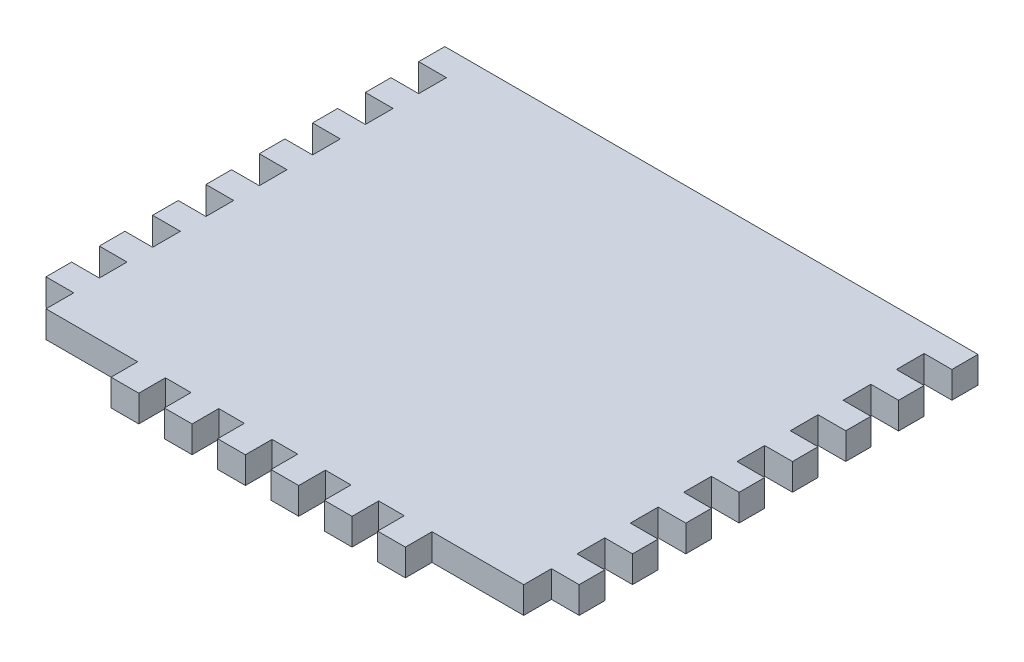
SolidWorks part; units mm, degrees
ref_plane "Front Plane" through (0, 0, 0) normal (0, 0, 1) x (1, 0, 0)
ref_plane "Top Plane" through (0, 0, 0) normal (0, 1, 0) x (1, 0, 0)
ref_plane "Right Plane" through (0, 0, 0) normal (1, 0, 0) x (0, 0, -1)
sketch "Sketch1" plane through (0, 0, 0) normal (0, 1, 0) x (1, 0, 0)
  line L1 (-63.5, -53.975) -> (63.5, -53.975)
  line L2 (-63.5, -53.975) -> (-63.5, 53.975)
  line L3 (-63.5, 53.975) -> (63.5, 53.975)
  line L4 (63.5, -53.975) -> (63.5, 53.975)
  line L5 (-63.5, -53.975) -> (63.5, 53.975) construction
  line L6 (-63.5, 53.975) -> (63.5, -53.975) construction
  line L11 (-41.275, -53.975) -> (41.275, 53.975) construction
  line L12 (-41.275, 53.975) -> (41.275, -53.975) construction
  point P0 (0, 0)
  point P5 (0, 0)
  dimension "D1" = 127
  dimension "D2" = 107.95
extrude "Boss-Extrude1" add sketch "Sketch1" along normal blind 6.35
sketch "Sketch2" plane through (0, 6.35, 0) normal (0, 1, 0) x (1, 0, 0)
  line L37 (22.352, -47.625) -> (28.448, -47.625)
  line L49 (28.448, -47.625) -> (28.448, -54.229)
  line L69 (0, 0) -> (0, -10.121) construction
  line L74 (-63.5, 53.975) -> (-63.5, -53.975) construction
  line L75 (-56.896, 28.448) -> (-63.5, 28.448)
  line L76 (-56.896, 28.448) -> (-56.896, 35.052)
  line L78 (-63.5, 28.448) -> (-63.5, 35.052)
  line L79 (-56.896, 22.479) -> (-63.5, 22.479)
  line L80 (-56.896, 22.479) -> (-56.896, 15.875)
  line L81 (-56.896, 15.875) -> (-63.5, 15.875)
  line L82 (-63.5, 22.479) -> (-63.5, 15.875)
  line L83 (-56.896, 9.779) -> (-63.5, 9.779)
  line L84 (-56.896, 9.779) -> (-56.896, 3.175)
  line L85 (-56.896, 3.175) -> (-63.5, 3.175)
  line L86 (-63.5, 9.779) -> (-63.5, 3.175)
  line L87 (-56.896, -2.921) -> (-63.5, -2.921)
  line L88 (-56.896, -2.921) -> (-56.896, -9.525)
  line L89 (-56.896, -9.525) -> (-63.5, -9.525)
  line L90 (-63.5, -2.921) -> (-63.5, -9.525)
  line L91 (-56.896, -15.621) -> (-63.5, -15.621)
  line L92 (-56.896, -15.621) -> (-56.896, -22.225)
  line L93 (-56.896, -22.225) -> (-63.5, -22.225)
  line L94 (-63.5, -15.621) -> (-63.5, -22.225)
  line L95 (-56.896, -28.321) -> (-63.5, -28.321)
  line L96 (-56.896, -28.321) -> (-56.896, -34.925)
  line L97 (-56.896, -34.925) -> (-63.5, -34.925)
  line L98 (-63.5, -28.321) -> (-63.5, -34.925)
  line L99 (-56.896, -41.021) -> (-63.5, -41.021)
  line L100 (-56.896, -41.021) -> (-56.896, -47.625)
  line L102 (-63.5, -41.021) -> (-63.5, -47.625)
  line L118 (63.5, -41.021) -> (63.5, -47.625)
  line L120 (56.896, -41.021) -> (56.896, -47.625)
  line L121 (56.896, -41.021) -> (63.5, -41.021)
  line L122 (63.5, -28.321) -> (63.5, -34.925)
  line L123 (56.896, -34.925) -> (63.5, -34.925)
  line L124 (56.896, -28.321) -> (56.896, -34.925)
  line L125 (56.896, -28.321) -> (63.5, -28.321)
  line L126 (63.5, -15.621) -> (63.5, -22.225)
  line L127 (56.896, -22.225) -> (63.5, -22.225)
  line L128 (56.896, -15.621) -> (56.896, -22.225)
  line L129 (56.896, -15.621) -> (63.5, -15.621)
  line L130 (63.5, -2.921) -> (63.5, -9.525)
  line L131 (56.896, -9.525) -> (63.5, -9.525)
  line L132 (56.896, -2.921) -> (56.896, -9.525)
  line L133 (56.896, -2.921) -> (63.5, -2.921)
  line L134 (63.5, 9.779) -> (63.5, 3.175)
  line L135 (56.896, 3.175) -> (63.5, 3.175)
  line L136 (56.896, 9.779) -> (56.896, 3.175)
  line L137 (56.896, 9.779) -> (63.5, 9.779)
  line L138 (63.5, 22.479) -> (63.5, 15.875)
  line L139 (56.896, 15.875) -> (63.5, 15.875)
  line L140 (56.896, 22.479) -> (56.896, 15.875)
  line L141 (56.896, 22.479) -> (63.5, 22.479)
  line L150 (-56.896, -53.721) -> (-63.5, -53.721) [skipped]
  line L151 (-56.896, -53.721) -> (-56.896, -60.325) [skipped]
  line L152 (-56.896, -60.325) -> (-63.5, -60.325) [skipped]
  line L153 (-63.5, -53.721) -> (-63.5, -60.325) [skipped]
  line L154 (-63.5, 35.052) -> (-56.896, 35.052)
  line L155 (63.5, 35.052) -> (56.896, 35.052)
  line L156 (63.5, 28.448) -> (63.5, 35.052)
  line L157 (56.896, 28.448) -> (56.896, 35.052)
  line L158 (56.896, 28.448) -> (63.5, 28.448)
  line L159 (-56.896, -47.625) -> (-35.052, -47.625)
  line L160 (-35.052, -47.625) -> (-35.052, -54.229)
  line L161 (-35.052, -54.229) -> (-28.448, -54.229)
  line L162 (-28.448, -54.229) -> (-28.448, -47.625)
  line L163 (-28.448, -47.625) -> (-22.352, -47.625)
  line L164 (-22.352, -47.625) -> (-22.352, -54.229)
  line L165 (-22.352, -54.229) -> (-15.748, -54.229)
  line L166 (-15.748, -54.229) -> (-15.748, -47.625)
  line L167 (-15.748, -47.625) -> (-9.652, -47.625)
  line L168 (-9.652, -47.625) -> (-9.652, -54.229)
  line L169 (-9.652, -54.229) -> (-3.048, -54.229)
  line L170 (-3.048, -54.229) -> (-3.048, -47.625)
  line L171 (-3.048, -47.625) -> (3.048, -47.625)
  line L172 (3.048, -47.625) -> (3.048, -54.229)
  line L173 (3.048, -54.229) -> (9.652, -54.229)
  line L174 (9.652, -54.229) -> (9.652, -47.625)
  line L175 (9.652, -47.625) -> (15.748, -47.625)
  line L176 (15.748, -47.625) -> (15.748, -54.229)
  line L177 (15.748, -54.229) -> (22.352, -54.229)
  line L178 (22.352, -54.229) -> (22.352, -47.625)
  line L180 (-63.5, -47.625) -> (-63.5, -92.545)
  line L181 (-56.896, -47.625) -> (-63.5, -47.625) [skipped]
  line L182 (-63.5, -92.545) -> (63.5, -92.545)
  line L183 (63.5, -92.545) -> (63.5, -47.625)
  line L184 (28.448, -54.229) -> (35.052, -54.229)
  line L185 (35.052, -54.229) -> (35.052, -47.625)
  line L186 (35.052, -47.625) -> (56.896, -47.625)
  line L187 (63.5, 53.975) -> (-63.5, 53.975) construction
  line L188 (63.5, 47.752) -> (56.896, 47.752)
  line L189 (63.5, 41.148) -> (63.5, 47.752)
  line L190 (56.896, 41.148) -> (56.896, 47.752)
  line L191 (56.896, 41.148) -> (63.5, 41.148)
  line L192 (-56.896, 41.148) -> (-63.5, 41.148)
  line L193 (-56.896, 41.148) -> (-56.896, 47.752)
  line L194 (-63.5, 41.148) -> (-63.5, 47.752)
  line L195 (-63.5, 47.752) -> (-56.896, 47.752)
  point P0 (-28.448, -50.927)
  dimension "D3" = 6.604
  dimension "D5" = 6.096
  dimension "D6" = 101.6
  dimension "D7" = 6.604
  dimension "D8" = 6.604
  dimension "D9" = 2
  dimension "D10" = 6.604
  dimension "D12" = 2
  dimension "D4" = 6.096
  dimension "D14" = 5.969
  dimension "D11" = 7
extrude "Cut-Extrude1" cut sketch "Sketch2" against normal through all both and the other way through all
